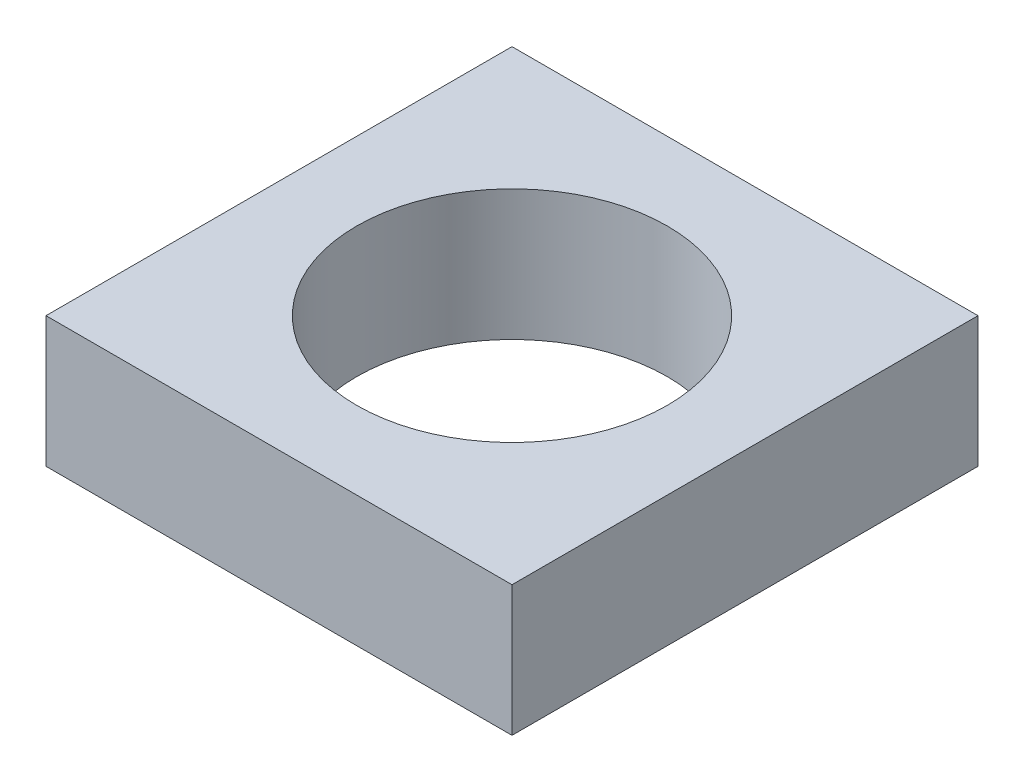
SolidWorks part; units mm, degrees
ref_plane "Front Plane" through (0, 0, 0) normal (0, 0, 1) x (1, 0, 0)
ref_plane "Top Plane" through (0, 0, 0) normal (0, 1, 0) x (1, 0, 0)
ref_plane "Right Plane" through (0, 0, 0) normal (1, 0, 0) x (0, 0, -1)
sketch "Sketch1" plane through (0, 0, 0) normal (0, 1, 0) x (1, 0, 0)
  line L1 (-19.05, -19.05) -> (19.05, -19.05)
  line L2 (-19.05, -19.05) -> (-19.05, 19.05)
  line L3 (-19.05, 19.05) -> (19.05, 19.05)
  line L4 (19.05, -19.05) -> (19.05, 19.05)
  line L5 (-19.05, -19.05) -> (19.05, 19.05) construction
  line L6 (-19.05, 19.05) -> (19.05, -19.05) construction
  point P0 (0, 0)
  dimension "D1" = 38.1
  dimension "D2" = 38.1
extrude "Boss-Extrude1" add sketch "Sketch1" along normal blind 10.668
sketch "Sketch3" plane through (0, 10.668, 0) normal (0, 1, 0) x (1, 0, 0)
  circle A0 centre (0, 0) radius 12.7
  point P3 (0, 0)
  dimension "D1" = 25.4
extrude "Cut-Extrude1" cut sketch "Sketch3" against normal blind 10.668 contours A0
